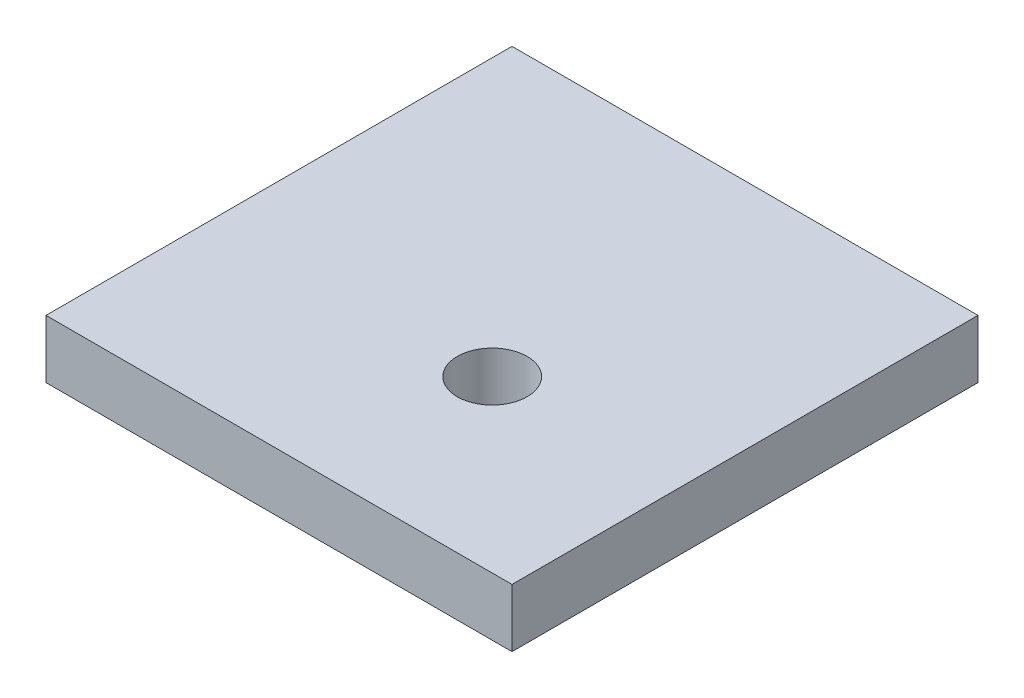
SolidWorks part; units mm, degrees
ref_plane "Front Plane" through (0, 0, 0) normal (0, 0, 1) x (1, 0, 0)
ref_plane "Top Plane" through (0, 0, 0) normal (0, 1, 0) x (1, 0, 0)
ref_plane "Right Plane" through (0, 0, 0) normal (1, 0, 0) x (0, 0, -1)
sketch "Sketch2" plane through (0, 0, 0) normal (0, 0, 1) x (1, 0, 0)
  line L1 (-200, -25) -> (200, -25)
  line L2 (-200, -25) -> (-200, 25)
  line L3 (-200, 25) -> (200, 25)
  line L4 (200, -25) -> (200, 25)
  line L5 (-200, -25) -> (200, 25) construction
  line L6 (-200, 25) -> (200, -25) construction
  point P0 (0, 0)
  dimension "D1" = 50
  dimension "D2" = 400
extrude "Boss-Extrude1" add sketch "Sketch2" along normal blind 400
sketch "Sketch3" plane through (0, 25, 0) normal (0, 1, 0) x (1, 0, 0)
  line L0 (200, 0) -> (37, 0) construction
  line L1 (200, 0) -> (-200, 0) construction
  line L2 (37, 0) -> (37, -254) construction
  circle A0 centre (37, -254) radius 30
  dimension "D3" = 60
  dimension "D1" = 163
  dimension "D2" = 254
extrude "Cut-Extrude1" cut sketch "Sketch3" against normal through all
